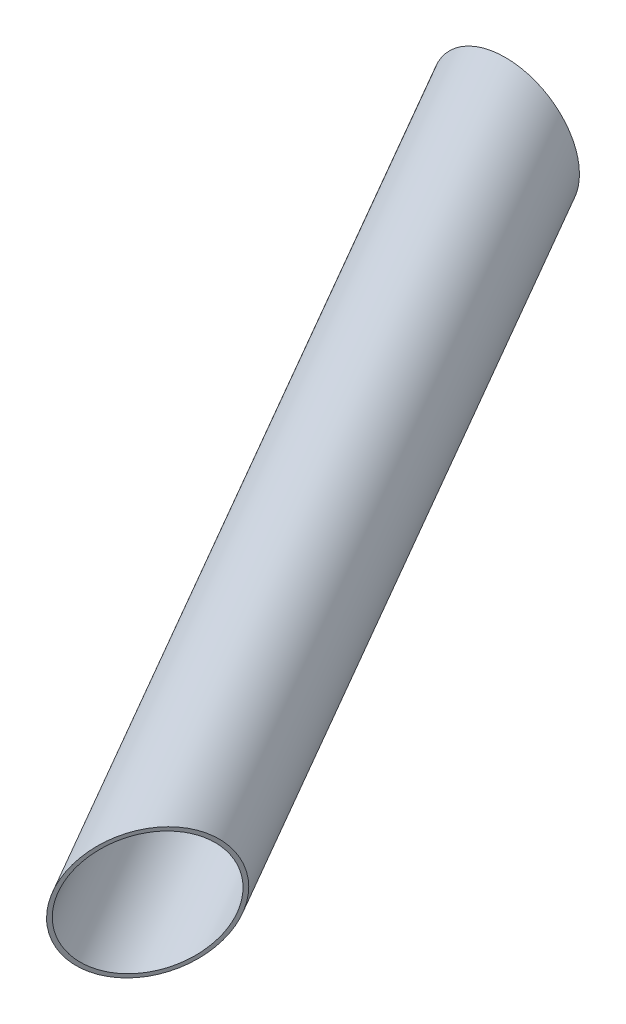
SolidWorks part; units mm, degrees
ref_plane "Front Plane" through (0, 0, 0) normal (0, 0, 1) x (1, 0, 0)
ref_plane "Top Plane" through (0, 0, 0) normal (0, 1, 0) x (1, 0, 0)
ref_plane "Right Plane" through (0, 0, 0) normal (1, 0, 0) x (0, 0, -1)
sketch "Sketch2" plane through (0, 0, 0) normal (0, 1, 0) x (1, 0, 0)
  line L1 (-404.1452, -700) -> (404.1452, -700)
  line L2 (404.1452, -700) -> (808.2904, 0)
  line L3 (808.2904, 0) -> (404.1452, 700)
  line L4 (404.1452, 700) -> (-404.1452, 700)
  line L5 (-404.1452, 700) -> (-808.2904, 0)
  line L6 (-808.2904, 0) -> (-404.1452, -700)
  circle A0 centre (0, 0) radius 700 construction
  dimension "D1" = 700
sketch "Sketch3" plane through (0, 0, 0) normal (1, 0, 0) x (0, 0, -1)
  circle A0 centre (-700, 0) radius 50
  circle A1 centre (-700, 0) radius 53
  dimension "D1" = 100
  dimension "D2" = 3
sweep "Sweep1" add profiles "Sketch3" path "Sketch2"
sketch "Sketch4" plane through (0, 0, 0) normal (0, 1, 0) x (1, 0, 0)
  line L0 (0, 0) -> (-492.2503, -852.6025)
  line L1 (-984.5006, 0) -> (0, 0)
  circle A0 centre (0, 0) radius 984.5006 construction
split "Split1" trim tools "Sketch4" bodies to split 101 resulting bodies 102
